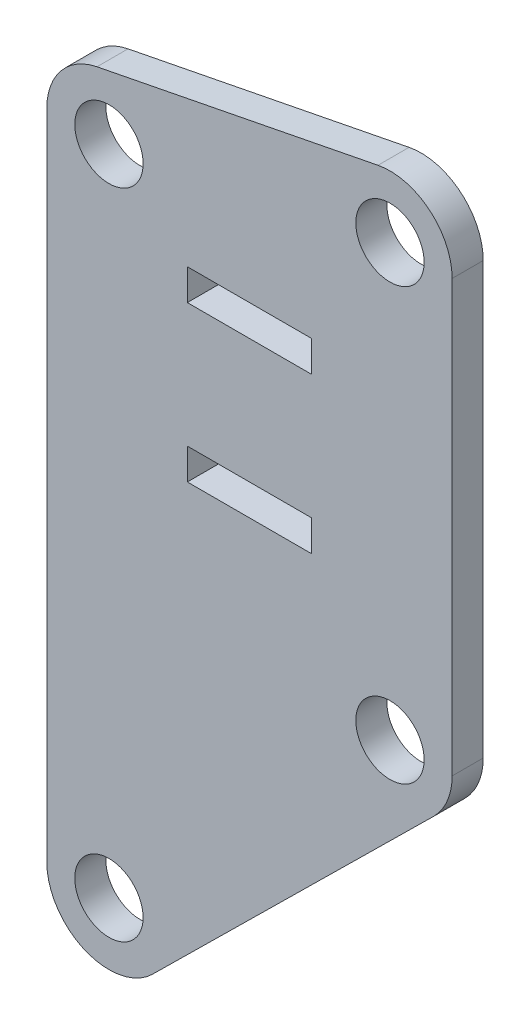
SolidWorks part; units mm, degrees
material "AISI 4340 Сталь, отожженная"
ref_plane "Спереди" through (0, 0, 0) normal (0, 0, 1) x (1, 0, 0)
ref_plane "Сверху" through (0, 0, 0) normal (0, 1, 0) x (1, 0, 0)
ref_plane "Справа" through (0, 0, 0) normal (1, 0, 0) x (0, 0, -1)
sketch "Эскиз1" plane through (0, 0, 0) normal (0, 0, 1) x (1, 0, 0)
  line L0 (-15.5904, -64.0893) -> (29.6348, -19.4825)
  line L1 (32.6126, -12.3629) -> (32.6126, 56.9697)
  line L2 (20.6847, 66.7821) -> (-24.5405, 57.8966)
  line L3 (-32.6126, 48.0842) -> (-32.6126, -56.9697)
  arc A0 (29.6348, -19.4825) -> (32.6126, -12.3629) centre (22.6126, -12.3629) ccw
  arc A1 (32.6126, 56.9697) -> (20.6847, 66.7821) centre (22.6126, 56.9697) ccw
  arc A2 (-24.5405, 57.8966) -> (-32.6126, 48.0842) centre (-22.6126, 48.0842) ccw
  arc A3 (-32.6126, -56.9697) -> (-15.5904, -64.0893) centre (-22.6126, -56.9697) ccw
extrude "Бобышка-Вытянуть1" add sketch "Эскиз1" along normal blind 5
sketch "Эскиз2" plane through (0, 0, 5) normal (0, 0, 1) x (1, 0, 0)
  line L0 (32.6126, 22.3034) -> (-32.6126, 22.3034) construction
  line L1 (32.6126, -12.3629) -> (32.6126, 56.9697) construction
  line L2 (-32.6126, 48.0842) -> (-32.6126, -56.9697) construction
  line L3 (10, 32.3034) -> (-10, 32.3034)
  line L4 (10, 12.3034) -> (-10, 12.3034)
  line L5 (10, 37.3034) -> (-10, 37.3034)
  line L6 (0, 32.3034) -> (0, 37.3034) construction
  line L7 (10, 32.3034) -> (10, 37.3034)
  line L8 (-10, 32.3034) -> (-10, 37.3034)
  line L9 (10, 7.3034) -> (-10, 7.3034)
  line L10 (0, 12.3034) -> (0, 7.3034) construction
  line L11 (-10, 12.3034) -> (-10, 7.3034)
  line L12 (10, 12.3034) -> (10, 7.3034)
  line L13 (32.6126, 7.3034) -> (-32.6126, 7.3034) construction
  line L14 (32.6126, 12.3034) -> (-32.6126, 12.3034) construction
  dimension "D1" = 5
  dimension "D2" = 10
  dimension "D4" = 10
  dimension "D5" = 10
extrude "Вырез-Вытянуть1" cut sketch "Эскиз2" against normal through all
sketch "Эскиз3" plane through (0, 0, 5) normal (0, 0, 1) x (1, 0, 0)
  circle A1 centre (22.6126, 56.9697) radius 5.5
  circle A3 centre (-22.6126, -56.9697) radius 5.5
  circle A4 centre (-22.6126, 48.0842) radius 5.5
  circle A5 centre (22.6126, -12.3629) radius 5.5
  dimension "D1" = 11
  dimension "D2" = 11
  dimension "D3" = 11
  dimension "D4" = 11
extrude "Вырез-Вытянуть2" cut sketch "Эскиз3" against normal through all
